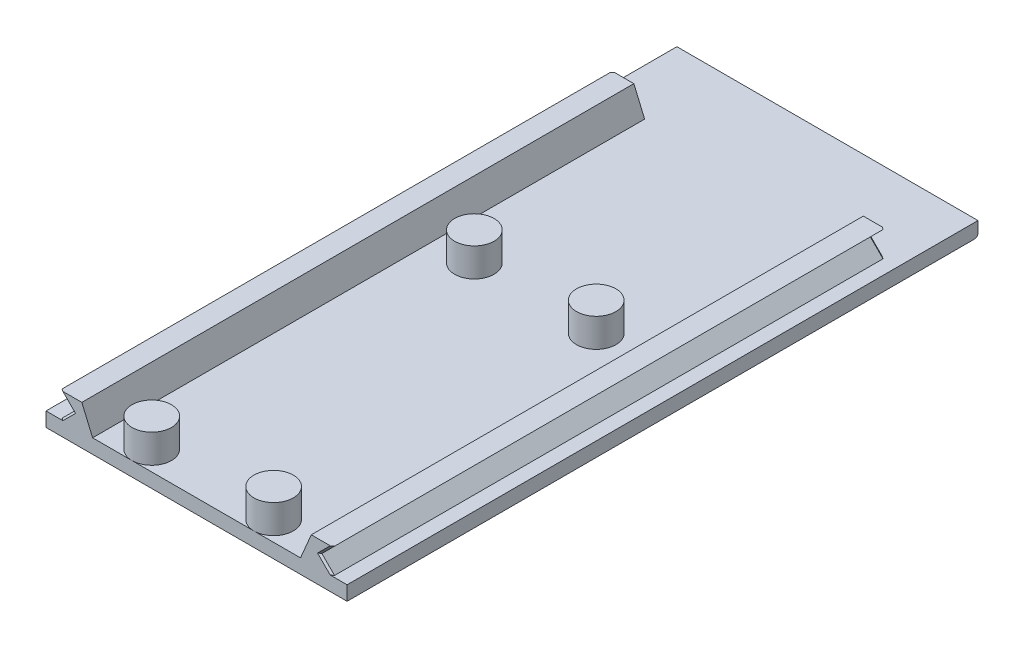
SolidWorks part; units mm, degrees
ref_plane "Front Plane" through (0, 0, 0) normal (0, 0, 1) x (1, 0, 0)
ref_plane "Top Plane" through (0, 0, 0) normal (0, 1, 0) x (1, 0, 0)
ref_plane "Right Plane" through (0, 0, 0) normal (1, 0, 0) x (0, 0, -1)
sketch "Sketch1" plane through (0, 0, 0) normal (0, 1, 0) x (1, 0, 0)
  line L1 (-21, 44) -> (21, 44)
  line L2 (-21, 44) -> (-21, -44)
  line L3 (-21, -44) -> (21, -44)
  line L4 (21, 44) -> (21, -44)
  line L5 (-21, 44) -> (21, -44) construction
  line L6 (-21, -44) -> (21, 44) construction
  point P0 (0, 0)
  dimension "D1" = 88
  dimension "D2" = 42
extrude "Boss-Extrude1" add sketch "Sketch1" along normal blind 2
sketch "Sketch2" plane through (0, 0, 44) normal (0, 0, 1) x (1, 0, 0)
  line L0 (14.5, 2) -> (16, 5.5355)
  line L1 (-21, 2) -> (21, 2) construction
  line L2 (16, 5.5355) -> (19, 5.5355)
  line L3 (19, 5.5355) -> (17.2322, 3.7678)
  line L4 (17.2322, 3.7678) -> (19, 2)
  line L5 (19, 2) -> (14.5, 2)
  point P7 (14, 2)
  point P9 (0.1749, 9.6202)
  dimension "D1" = 3
  dimension "D2" = 4.5
  dimension "D3" = 2
  dimension "D4" = 45
  dimension "D5" = 2.5
  dimension "D6" = 2.5
  dimension "D7" = 90
extrude "Boss-Extrude2" add sketch "Sketch2" against normal blind 77
ref_plane "Plane1" through (0, 0, 0) normal (1, 0, 0) x (0, 0, -1)
mirror "Mirror1" about plane through (0, 0, 0) normal (1, 0, 0) of "Boss-Extrude2", "Boss-Extrude1"
sketch "Sketch3" plane through (0, 2, 0) normal (0, 1, 0) x (1, 0, 0)
  line L0 (-14.5, -44) -> (14.5, -44) construction
  line L1 (-21, 44) -> (-21, -44) construction
  circle A0 centre (-9, -41.25) radius 2.75
  circle A1 centre (8, -41.25) radius 2.75
  circle A2 centre (8, 3.75) radius 2.75
  circle A3 centre (-9, 3.75) radius 2.75
  dimension "D1" = 5.5
  dimension "D2" = 2.75
  dimension "D3" = 12
  dimension "D4" = 2
  dimension "D5" = 2
extrude "Boss-Extrude3" add sketch "Sketch3" along normal blind 4
fillet "Fillet1" radius 0.5 1 edges at (0, 0, -44)
chamfer "Chamfer3" distance 0.25 angle 45 8 edges at (-18.1161, 2.8839, 44) (-18.1161, 2.8839, -33) (-18.1161, 4.6517, 44) (-18.1161, 4.6517, -33) (18.1161, 2.8839, 44) (18.1161, 2.8839, -33) (18.1161, 4.6517, 44) (18.1161, 4.6517, -33)
